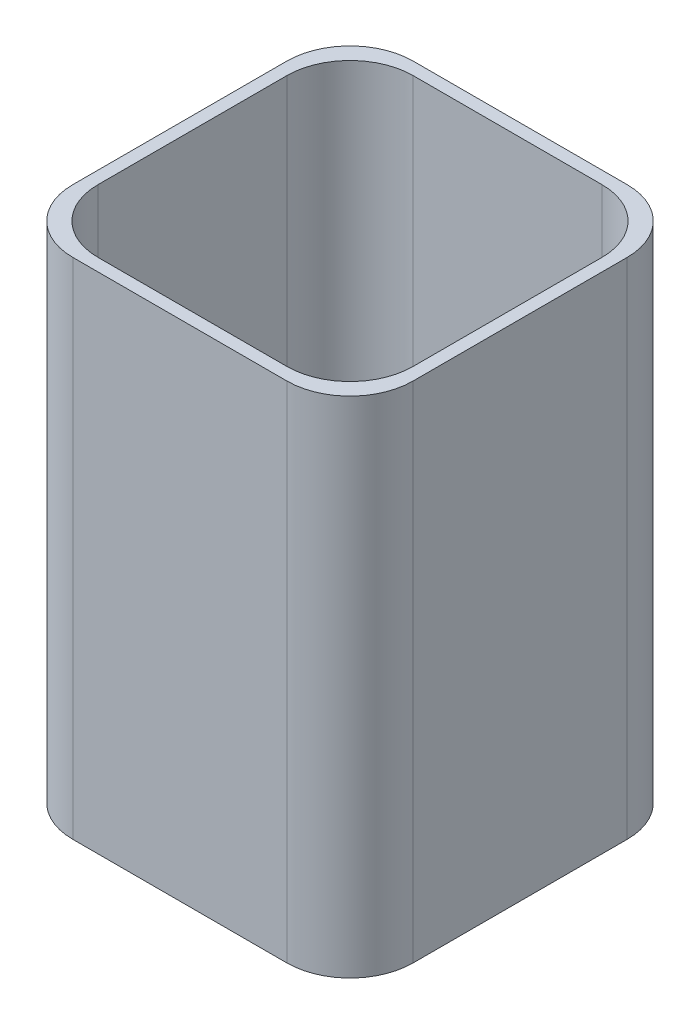
SolidWorks part; units mm, degrees
ref_plane "Front Plane" through (0, 0, 0) normal (0, 0, 1) x (1, 0, 0)
ref_plane "Top Plane" through (0, 0, 0) normal (0, 1, 0) x (1, 0, 0)
ref_plane "Right Plane" through (0, 0, 0) normal (1, 0, 0) x (0, 0, -1)
sketch "Sketch2" plane through (0, 0, 0) normal (0, 1, 0) x (1, 0, 0)
  line L1 (-80.3315, 46.4451) -> (-26.3315, 46.4451)
  line L2 (-80.3315, 46.4451) -> (-80.3315, -7.5549)
  line L3 (-80.3315, -7.5549) -> (-26.3315, -7.5549)
  line L4 (-26.3315, 46.4451) -> (-26.3315, -7.5549)
  dimension "D1" = 54
  dimension "D2" = 54
extrude "Boss-Extrude1" add sketch "Sketch2" along normal blind 80
sketch "Sketch3" plane through (0, 80, 0) normal (0, 1, 0) x (1, 0, 0)
  line L0 (-80.3315, 46.4451) -> (-80.3315, -7.5549) construction
  line L1 (-78.3315, 44.4451) -> (-28.3315, 44.4451)
  line L2 (-78.3315, 44.4451) -> (-78.3315, -5.5549)
  line L3 (-78.3315, -5.5549) -> (-28.3315, -5.5549)
  line L4 (-28.3315, 44.4451) -> (-28.3315, -5.5549)
  line L5 (-26.3315, 46.4451) -> (-80.3315, 46.4451) construction
  dimension "D1" = 2
  dimension "D2" = 2
  dimension "D3" = 50
  dimension "D4" = 50
extrude "Cut-Extrude1" cut sketch "Sketch3" against normal blind 78
fillet "Fillet2" radius 10 4 edges at (-78.3315, 41, 5.5549) (-78.3315, 41, -44.4451) (-28.3315, 41, 5.5549) (-28.3315, 41, -44.4451)
fillet "Fillet3" radius 10 4 edges at (-80.3315, 40, -46.4451) (-26.3315, 40, -46.4451) (-26.3315, 40, 7.5549) (-80.3315, 40, 7.5549)
